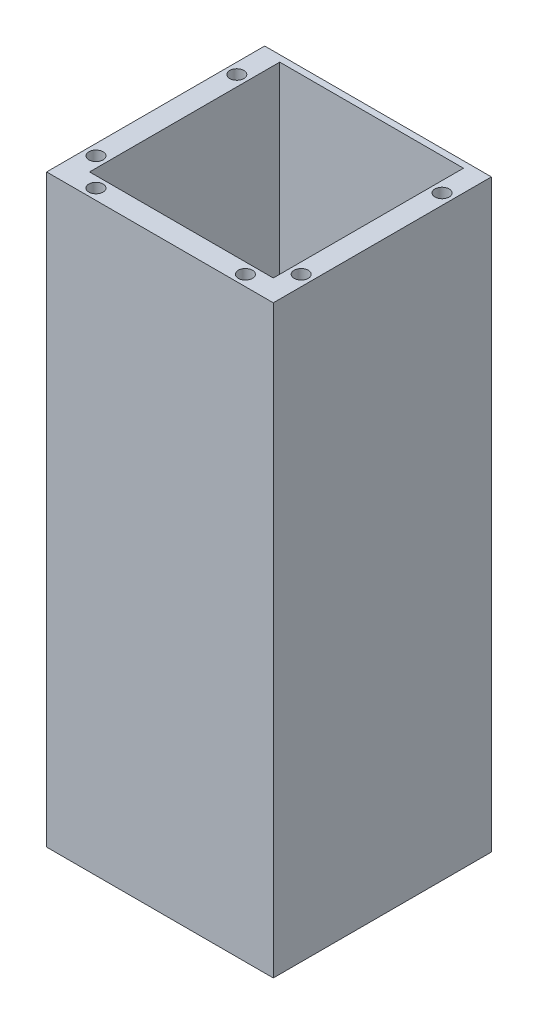
SolidWorks part; units mm, degrees
ref_plane "Plan de face" through (0, 0, 0) normal (0, 0, 1) x (1, 0, 0)
ref_plane "Plan de dessus" through (0, 0, 0) normal (0, 1, 0) x (1, 0, 0)
ref_plane "Plan de droite" through (0, 0, 0) normal (1, 0, 0) x (0, 0, -1)
sketch "Esquisse1" plane through (0, 0, 0) normal (0, 0, 1) x (1, 0, 0)
  line L1 (-57.9892, 54.9792) -> (47.6108, 54.9792)
  line L2 (-57.9892, 54.9792) -> (-57.9892, -217.4208)
  line L3 (-57.9892, -217.4208) -> (47.6108, -217.4208)
  line L4 (47.6108, 54.9792) -> (47.6108, -217.4208)
  dimension "D1" = 105.6
  dimension "D2" = 272.4
extrude "Boss.-Extru.1" add sketch "Esquisse1" along normal blind 101.6
sketch "Esquisse3" plane through (0, 54.9792, 0) normal (0, 1, 0) x (1, 0, 0)
  line L0 (47.6108, 0) -> (-57.9892, 0) construction
  line L1 (-47.9892, -3) -> (37.6108, -3)
  line L2 (-47.9892, -3) -> (-47.9892, -91.6)
  line L3 (-47.9892, -91.6) -> (37.6108, -91.6)
  line L4 (37.6108, -3) -> (37.6108, -91.6)
  line L5 (47.6108, -101.6) -> (-57.9892, -101.6) construction
  line L6 (-57.9892, -101.6) -> (-57.9892, 0) construction
  line L7 (47.6108, -101.6) -> (47.6108, 0) construction
  dimension "D1" = 3
  dimension "D2" = 10
  dimension "D3" = 10
  dimension "D4" = 10
extrude "Enlèv. mat.-Extru.1" cut sketch "Esquisse3" against normal blind 262.4
sketch "Esquisse4" plane through (0, -217.4208, 0) normal (0, -1, 0) x (1, 0, 0)
  line L0 (-57.9892, 101.6) -> (47.6108, 101.6) construction
  line L1 (-47.9892, 91.6) -> (37.6108, 91.6)
  line L2 (-47.9892, 91.6) -> (-47.9892, 71.6)
  line L3 (-47.9892, 71.6) -> (37.6108, 71.6)
  line L4 (37.6108, 91.6) -> (37.6108, 71.6)
  line L5 (-57.9892, 101.6) -> (-57.9892, 0) construction
  line L6 (47.6108, 101.6) -> (47.6108, 0) construction
  dimension "D1" = 10
  dimension "D2" = 10
  dimension "D3" = 10
  dimension "D4" = 20
extrude "Enlèv. mat.-Extru.2" cut sketch "Esquisse4" against normal blind 30
sketch "Esquisse5" plane through (0, 0, 0) normal (0, 0, -1) x (-1, 0, 0)
  line L0 (57.9892, -217.4208) -> (-47.6108, -217.4208) construction
  line L1 (-37.6108, -141.8208) -> (47.9892, -141.8208)
  line L2 (-37.6108, -141.8208) -> (-37.6108, -207.4208)
  line L3 (-37.6108, -207.4208) -> (47.9892, -207.4208)
  line L4 (47.9892, -141.8208) -> (47.9892, -207.4208)
  line L5 (-47.6108, -217.4208) -> (-47.6108, 54.9792) construction
  dimension "D1" = 10
  dimension "D2" = 65.6
  dimension "D3" = 85.6
  dimension "D4" = 10
extrude "Enlèv. mat.-Extru.3" cut sketch "Esquisse5" against normal blind 30
hole_wizard "Dégagement M61" positions "Esquisse3D1" profile "Esquisse8" hole size "M6" standard "Iso"
sketch3d "Esquisse3D1"
  line L0 (47.6108, 54.9792, 0) -> (-57.9892, 54.9792, 0) construction
  line L1 (-57.9892, 54.9792, 101.6) -> (-57.9892, 54.9792, 0) construction
  line L2 (47.6108, 54.9792, 101.6) -> (-57.9892, 54.9792, 101.6) construction
  line L3 (47.6108, 54.9792, 101.6) -> (47.6108, 54.9792, 0) construction
  point P2 (-52.9892, 54.9792, 18)
  point P9 (-52.9892, 54.9792, 83.6)
  point P14 (42.6108, 54.9792, 18)
  point P19 (42.6108, 54.9792, 83.6)
  point P22 (-39.9892, 54.9792, 96.6)
  point P24 (29.6108, 54.9792, 96.6)
  dimension "D1" = 18
  dimension "D2" = 5
  dimension "D3" = 5
  dimension "D4" = 18
  dimension "D5" = 18
  dimension "D6" = 5
  dimension "D7" = 5
  dimension "D8" = 18
  dimension "D9" = 5
  dimension "D10" = 5
  dimension "D11" = 18
  dimension "D12" = 18
sketch "Esquisse8" plane through (-52.9892, 54.9792, 18) normal (1, 0, 0) x (0, 0, 1)
  line L0 (0, 0) -> (0, 11.9828)
  line L1 (0, 11.9828) -> (3.3, 10)
  line L2 (3.3, 10) -> (3.3, 0)
  line L5 (3.3, 0) -> (0, 0)
  line L10 (0, 11.9828) -> (-3.3, 10) construction
  line L11 (0, -6.35) -> (0, 107.95) construction
  dimension "Diamètre du perçage" = 6.6
  dimension "Profondeur du perçage" = 10
  dimension "Angle de pointe" = 118
